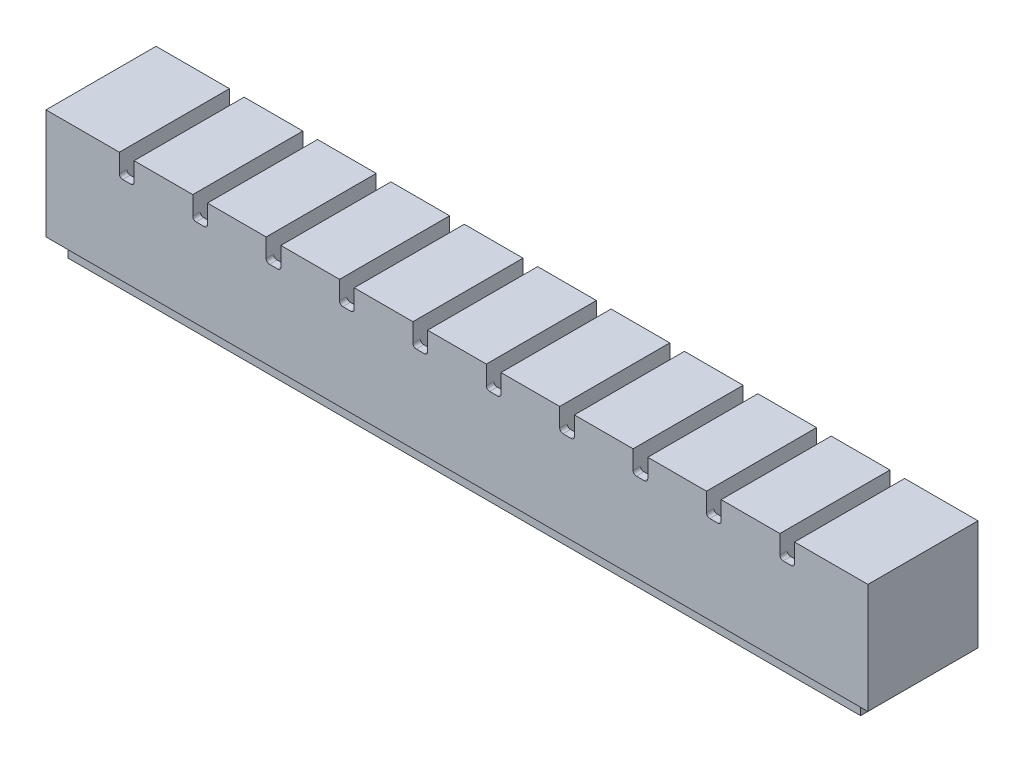
SolidWorks part; units mm, degrees
ref_plane "Front Plane" through (0, 0, 0) normal (0, 0, 1) x (1, 0, 0)
ref_plane "Top Plane" through (0, 0, 0) normal (0, 1, 0) x (1, 0, 0)
ref_plane "Right Plane" through (0, 0, 0) normal (1, 0, 0) x (0, 0, -1)
sketch "Sketch1" plane through (0, 0, 0) normal (0, 0, 1) x (1, 0, 0)
  line L1 (0, 0) -> (8, 0)
  line L2 (0, 0) -> (0, 15)
  line L3 (0, 15) -> (8, 15)
  line L4 (8, 0) -> (8, 15)
  dimension "D1" = 8
  dimension "D2" = 15
extrude "first chamber block" add sketch "Sketch1" along normal blind 15
sketch "Sketch2" plane through (0, 0, 0) normal (0, -1, 0) x (1, 0, 0)
  line L0 (8, 15) -> (8, 0) construction
  line L1 (1, 13) -> (7, 13)
  line L2 (1, 13) -> (1, 2)
  line L3 (1, 2) -> (7, 2)
  line L4 (7, 13) -> (7, 2)
  line L5 (0, 15) -> (0, 0) construction
  line L6 (0, 15) -> (8, 15) construction
  line L7 (0, 0) -> (8, 0) construction
  dimension "D1" = 1
  dimension "D2" = 1
  dimension "D3" = 2
  dimension "D4" = 2
extrude "first chamber cavity" cut sketch "Sketch2" against normal blind 13
sketch "Sketch3" plane through (8, 0, 0) normal (1, 0, 0) x (0, 0, -1)
  line L0 (-15, 0) -> (-15, 15) construction
  line L1 (0, 0) -> (-15, 0)
  line L2 (0, 0) -> (0, 3)
  line L3 (0, 3) -> (-15, 3)
  line L4 (-15, 0) -> (-15, 3)
  dimension "D1" = 3
extrude "chamber spacer" add sketch "Sketch3" along normal blind 2
pattern_linear "pattern chambers" count 11 spacing 10 along (1, 0, 0) of "chamber spacer", "first chamber cavity", "first chamber block"
combine bodies "combine into 1 solid body" operation type add bodies to combine 123 122 121 120 119 118 117 116 115 114 103
sketch "Sketch4" plane through (108, 0, 0) normal (1, 0, 0) x (0, 0, -1)
  line L1 (0, 15) -> (-15, 15)
  line L2 (0, 15) -> (0, 3)
  line L3 (0, 3) -> (-15, 3)
  line L4 (-15, 15) -> (-15, 3)
extrude "thicken end 1" add sketch "Sketch4" along normal up to surface (2 mm away) up to face at (110, 1.5, 7.5)
sketch "Sketch5" plane through (0, 0, 0) normal (-1, 0, 0) x (0, 0, 1)
  line L1 (15, 15) -> (0, 15)
  line L2 (15, 15) -> (15, 0)
  line L3 (15, 0) -> (0, 0)
  line L4 (0, 15) -> (0, 0)
extrude "thicken end 2" add sketch "Sketch5" along normal blind 2
ref_point "center of bottom face"
sketch "Sketch6" plane through (0, 0, 0) normal (0, -1, 0) x (1, 0, 0)
  line L0 (7, 2) -> (7, 13) construction
  line L1 (101, 6.5) -> (7, 6.5)
  line L2 (101, 6.5) -> (101, 8.5)
  line L3 (101, 8.5) -> (7, 8.5)
  line L4 (7, 6.5) -> (7, 8.5)
  line L5 (101, 6.5) -> (7, 8.5) construction
  line L6 (101, 8.5) -> (7, 6.5) construction
  point P0 (54, 7.5)
  dimension "D1" = 2
extrude "central air channel" cut sketch "Sketch6" against normal blind 2
sketch "Sketch7" plane through (0, 0, 0) normal (0, -1, 0) x (1, 0, 0)
  line L0 (0, 14) -> (108, 14)
  line L1 (1, 13) -> (107, 13)
  line L2 (1, 13) -> (1, 2)
  line L3 (1, 2) -> (107, 2)
  line L4 (107, 13) -> (107, 2)
  line L5 (108, 14) -> (108, 1)
  line L6 (0, 1) -> (108, 1)
  line L7 (0, 14) -> (0, 1)
  dimension "D1" = 1
extrude "bonding ridge" add sketch "Sketch7" along normal blind 2
sketch "Sketch9" plane through (0, 0, 0) normal (0, -1, 0) x (1, 0, 0)
  line L0 (11, 8.5) -> (11, 13) construction
  line L1 (11, 13) -> (7, 13) construction
  line L2 (7, 13) -> (7, 8.5) construction
  line L3 (7, 8.5) -> (11, 8.5) construction
  line L4 (7, 6.5) -> (7, 2) construction
  line L5 (7, 2) -> (11, 2) construction
  line L6 (11, 2) -> (11, 6.5) construction
  line L7 (11, 6.5) -> (7, 6.5) construction
  line L8 (11, 8.5) -> (11, 13) construction
  line L9 (11, 13) -> (7, 13) construction
  line L10 (7, 13) -> (7, 8.5) construction
  line L11 (7, 8.5) -> (11, 8.5) construction
  line L12 (7, 6.5) -> (7, 2) construction
  line L13 (7, 2) -> (11, 2) construction
  line L14 (11, 2) -> (11, 6.5) construction
  line L15 (11, 6.5) -> (7, 6.5) construction
  line L16 (10, 9.5) -> (10, 12)
  line L17 (10, 12) -> (8, 12)
  line L18 (8, 12) -> (8, 9.5)
  line L19 (8, 9.5) -> (10, 9.5)
  line L20 (8, 5.5) -> (8, 3)
  line L21 (8, 3) -> (10, 3)
  line L22 (10, 3) -> (10, 5.5)
  line L23 (10, 5.5) -> (8, 5.5)
  dimension "D1" = 1
extrude "bonding bumps" add sketch "Sketch9" along normal blind 2
pattern_linear "pattern bonding bumps" count 10 spacing 10 along (1, 0, 0) of "bonding bumps"
sketch "Skizze3" plane through (8, 0, 0) normal (1, 0, 0) x (0, 0, -1)
  line L0 (-15, 3) -> (-13.5, 3)
  line L1 (0, 3) -> (-15, 3) construction
  line L2 (-13.5, 3) -> (-14, 12.5)
  line L3 (-14, 12.5) -> (-15, 12.5)
  line L4 (-15, 3) -> (-15, 15) construction
  line L5 (-15, 12.5) -> (-15, 3)
  line L6 (-7.5, 15) -> (-7.5, -49985) construction
  line L7 (-15, 15) -> (0, 15) construction
  line L8 (0, 12.5) -> (0, 3)
  line L9 (-1, 12.5) -> (0, 12.5)
  line L10 (-1.5, 3) -> (-1, 12.5)
  line L11 (0, 3) -> (-1.5, 3)
  point P13 (-7.5, 15)
  dimension "D1" = 2.5
  dimension "D2" = 1.5
  dimension "D3" = 1
extrude "Aufsatz-Linear austragen3" add sketch "Skizze3" along normal up to next
sketch "Skizze5" plane through (0, 0, 0) normal (0, 0, -1) x (-1, 0, 0)
  line L0 (-10, 12.5) -> (-10, 3) construction
  line L1 (-10, 12.5) -> (-8, 12.5) construction
  line L2 (-8, 12.5) -> (-8, 3) construction
  line L3 (-10, 12.5) -> (-10, 3) construction
  line L4 (-10, 12.5) -> (-8, 12.5) construction
  line L5 (-8, 12.5) -> (-8, 3) construction
  line L7 (-10, 12.5) -> (-8, 12.5)
  line L8 (-10, 12.5) -> (-10, 12.45)
  line L9 (-9.55, 12) -> (-8.45, 12)
  line L10 (-8, 12.5) -> (-8, 12.45)
  arc A0 (-8.45, 12) -> (-8, 12.45) centre (-8.45, 12.45) ccw
  arc A1 (-10, 12.45) -> (-9.55, 12) centre (-9.55, 12.45) ccw
  point P9 (-8, 12)
  dimension "D1" = 0.45
  dimension "D2" = 0.5
extrude "Schnitt-Linear austragen2" cut sketch "Skizze5" against normal through all
pattern_linear "Lineares Muster8" count 10 spacing 10 along (1, 0, 0) of "Aufsatz-Linear austragen3", "Schnitt-Linear austragen2"
